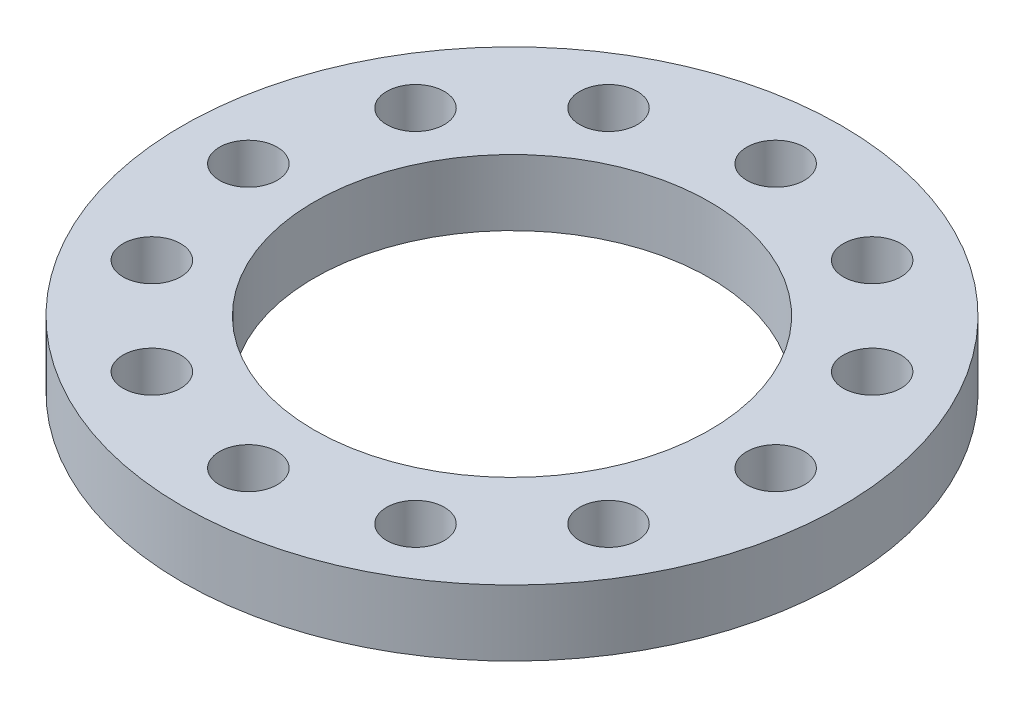
SolidWorks part; units mm, degrees
ref_plane "Plano frontal" through (0, 0, 0) normal (0, 0, 1) x (1, 0, 0)
ref_plane "Plano superior" through (0, 0, 0) normal (0, 1, 0) x (1, 0, 0)
ref_plane "Plano direito" through (0, 0, 0) normal (1, 0, 0) x (0, 0, -1)
sketch "Esboço1" plane through (0, 0, 0) normal (0, 1, 0) x (1, 0, 0)
  line L0 (0, 0) -> (0, -2.2527)
  circle A0 centre (0, 0) radius 20
  circle A1 centre (0, 0) radius 12
  circle A2 centre (-8, 13.8564) radius 1.75
  circle A3 centre (-13.8564, 8) radius 1.75
  circle A4 centre (-16, 0) radius 1.75
  circle A5 centre (-13.8564, -8) radius 1.75
  circle A6 centre (-8, -13.8564) radius 1.75
  circle A7 centre (8, -13.8564) radius 1.75
  circle A8 centre (0, -16) radius 1.75
  circle A9 centre (13.8564, -8) radius 1.75
  circle A10 centre (16, 0) radius 1.75
  circle A11 centre (13.8564, 8) radius 1.75
  circle A12 centre (8, 13.8564) radius 1.75
  circle A13 centre (0, 16) radius 1.75
extrude "Ressalto-extrusão1" add sketch "Esboço1" along normal blind 4 contours A0 A13 A12 A11 A10 A9 A8 A7 A6 A5 A4 A3 A2 A1
